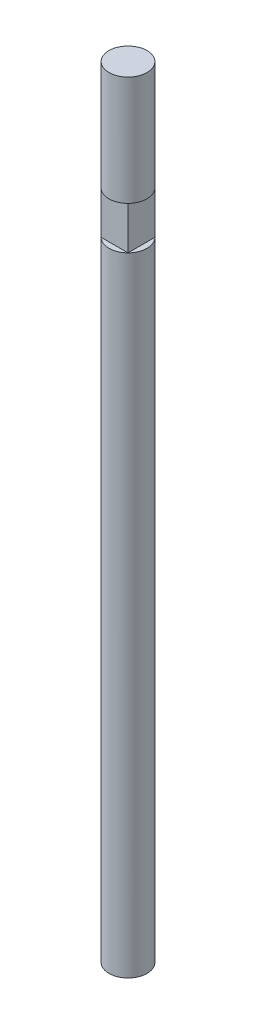
SolidWorks part; units mm, degrees
ref_plane "Alzado" through (0, 0, 0) normal (0, 0, 1) x (1, 0, 0)
ref_plane "Planta" through (0, 0, 0) normal (0, 1, 0) x (1, 0, 0)
ref_plane "Vista lateral" through (0, 0, 0) normal (1, 0, 0) x (0, 0, -1)
sketch "Croquis1" plane through (0, 0, 0) normal (0, 1, 0) x (1, 0, 0)
  circle A0 centre (0, 0) radius 2
  dimension "D1" = 4
extrude "Saliente-Extruir1" add sketch "Croquis1" along normal blind 82
ref_plane "Plano1" through (0, 70.5, 0) normal (0, 1, 0) x (1, 0, 0)
sketch "Croquis2" plane through (0, 70.5, 0) normal (0, 1, 0) x (1, 0, 0)
  line L1 (2, -2) -> (-1.4142, -2)
  line L3 (1.4142, -1.4142) -> (-1.4142, -1.4142)
  line L4 (-1.4142, -2) -> (-1.4142, -1.4142)
  line L6 (2, -2) -> (2, 1.4142)
  line L7 (2, 1.4142) -> (1.4142, 1.4142)
  line L8 (1.4142, -1.4142) -> (1.4142, 1.4142)
  circle A0 centre (0, 0) radius 2 construction
extrude "Cortar-Extruir1" cut sketch "Croquis2" against normal blind 4.5
